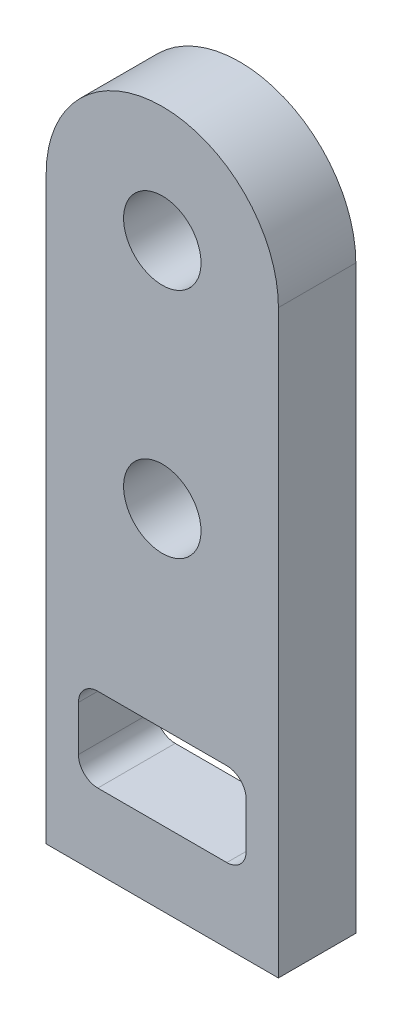
SolidWorks part; units mm, degrees
ref_plane "Alzado" through (0, 0, 0) normal (0, 0, 1) x (1, 0, 0)
ref_plane "Planta" through (0, 0, 0) normal (0, 1, 0) x (1, 0, 0)
ref_plane "Vista lateral" through (0, 0, 0) normal (1, 0, 0) x (0, 0, -1)
sketch "Model" plane through (0, 0, 0) normal (0, 0, 1) x (1, 0, 0)
  line L0 (159.5914, 221.494) -> (159.5914, 198.994)
  line L1 (159.5914, 198.994) -> (150.5914, 198.994)
  line L2 (150.5914, 198.994) -> (150.5914, 221.494)
  line L3 (157.5914, 201.869) -> (152.5914, 201.869)
  line L4 (151.8414, 202.619) -> (151.8414, 204.369)
  line L5 (152.5914, 205.119) -> (157.5914, 205.119)
  line L6 (158.3414, 204.369) -> (158.3414, 202.619)
  circle A0 centre (155.0914, 221.494) radius 1.5
  arc A1 (159.5914, 221.494) -> (150.5914, 221.494) centre (155.0914, 221.494) ccw
  arc A2 (151.8414, 202.619) -> (152.5914, 201.869) centre (152.5914, 202.619) ccw
  arc A3 (152.5914, 205.119) -> (151.8414, 204.369) centre (152.5914, 204.369) ccw
  arc A4 (158.3414, 204.369) -> (157.5914, 205.119) centre (157.5914, 204.369) ccw
  arc A5 (157.5914, 201.869) -> (158.3414, 202.619) centre (157.5914, 202.619) ccw
  circle A6 centre (155.0914, 212.494) radius 1.5
extrude "Saliente-Extruir1" add sketch "Model" along normal blind 3
